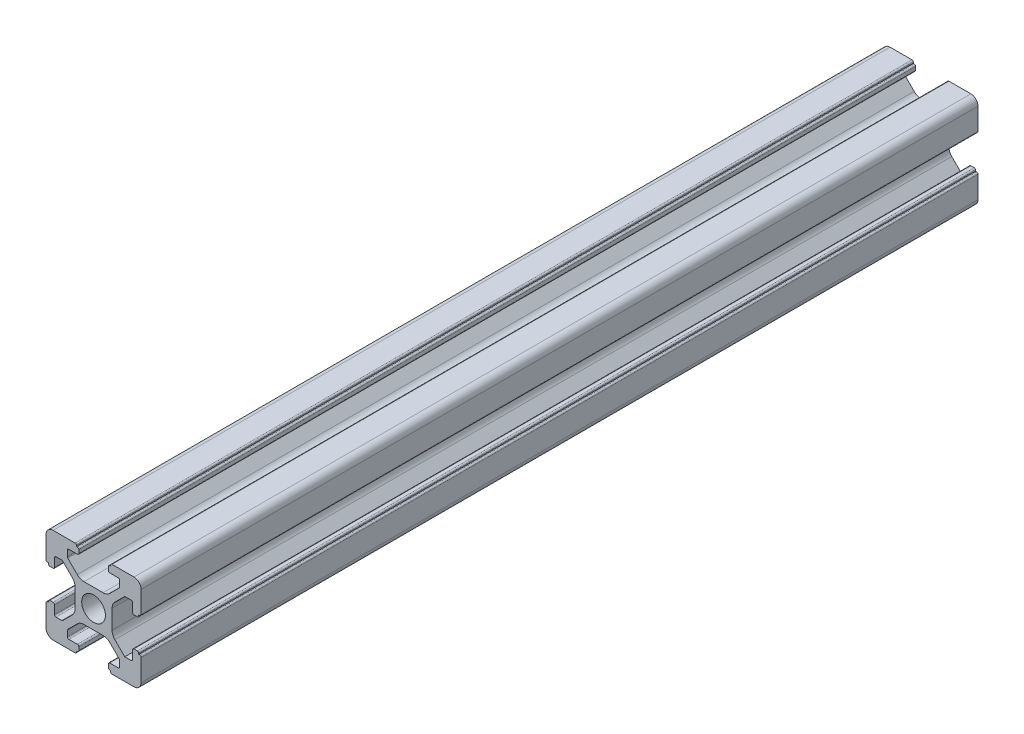
SolidWorks part; units mm, degrees
ref_plane "前视基准面" through (0, 0, 0) normal (0, 0, 1) x (1, 0, 0)
ref_plane "上视基准面" through (0, 0, 0) normal (0, 1, 0) x (1, 0, 0)
ref_plane "右视基准面" through (0, 0, 0) normal (1, 0, 0) x (0, 0, -1)
sketch "草图1" plane through (0, 0, 0) normal (0, 0, 1) x (1, 0, 0)
  line L0 (3.9, 0) -> (3.9, -2.0109)
  line L1 (4.4858, -3.4251) -> (6.5607, -5.5)
  line L2 (6.5607, -5.5) -> (7.9, -5.5)
  line L3 (8.2, -5.2) -> (8.2, -3.4)
  line L4 (8.5, -3.1) -> (9.2, -3.1)
  line L5 (9.5, -3.4) -> (9.5, -3.6)
  line L6 (9.5, -3.6) -> (9.7, -3.6)
  line L7 (10, -3.9) -> (10, -8.5)
  line L8 (8.5, -10) -> (3.9, -10)
  line L9 (3.1, -9.2) -> (3.1, -8.5)
  line L10 (3.4, -8.2) -> (5.2, -8.2)
  line L11 (5.5, -7.9) -> (5.5, -6.6849)
  line L12 (5.4121, -6.4728) -> (3.4251, -4.4858)
  line L13 (2.0109, -3.9) -> (0, -3.9)
  line L14 (0, -3.9) -> (-2.0109, -3.9)
  line L15 (-3.4251, -4.4858) -> (-5.4121, -6.4728)
  line L16 (-5.5, -6.6849) -> (-5.5, -7.9)
  line L17 (-5.2, -8.2) -> (-3.4, -8.2)
  line L18 (-3.1, -8.5) -> (-3.1, -9.2)
  line L19 (-3.9, -10) -> (-8.5, -10)
  line L20 (-10, -8.5) -> (-10, -3.9)
  line L21 (-9.7, -3.6) -> (-9.5, -3.6)
  line L22 (-9.5, -3.6) -> (-9.5, -3.4)
  line L23 (-9.2, -3.1) -> (-8.5, -3.1)
  line L24 (-8.2, -3.4) -> (-8.2, -5.2)
  line L25 (-7.9, -5.5) -> (-6.6849, -5.5)
  line L26 (-6.4728, -5.4121) -> (-4.4858, -3.4251)
  line L27 (-3.9, -2.0109) -> (-3.9, 0)
  line L28 (-3.9, 0) -> (-3.9, 2.0109)
  line L29 (-4.4858, 3.4251) -> (-6.4728, 5.4121)
  line L30 (-6.6849, 5.5) -> (-7.9, 5.5)
  line L31 (-8.2, 5.2) -> (-8.2, 3.4)
  line L32 (-8.5, 3.1) -> (-9.2, 3.1)
  line L33 (-9.5, 3.4) -> (-9.5, 3.6)
  line L34 (-9.5, 3.6) -> (-9.7, 3.6)
  line L35 (-10, 3.9) -> (-10, 8.5)
  line L36 (-8.5, 10) -> (-3.9, 10)
  line L37 (-3.6, 9.7) -> (-3.6, 9.5)
  line L38 (-3.6, 9.5) -> (-3.4, 9.5)
  line L39 (-3.1, 9.2) -> (-3.1, 8.5)
  line L40 (-3.4, 8.2) -> (-5.2, 8.2)
  line L41 (-5.5, 7.9) -> (-5.5, 6.6849)
  line L42 (-5.4121, 6.4728) -> (-3.4251, 4.4858)
  line L43 (-2.0109, 3.9) -> (0, 3.9)
  line L44 (0, 3.9) -> (2.0109, 3.9)
  line L45 (3.4251, 4.4858) -> (5.4121, 6.4728)
  line L46 (5.5, 6.6849) -> (5.5, 7.9)
  line L47 (5.2, 8.2) -> (3.4, 8.2)
  line L48 (3.1, 8.5) -> (3.1, 9.2)
  line L49 (3.4, 9.5) -> (3.6, 9.5)
  line L50 (3.6, 9.5) -> (3.6, 9.7)
  line L51 (3.9, 10) -> (8.5, 10)
  line L52 (10, 8.5) -> (10, 3.9)
  line L53 (9.7, 3.6) -> (9.5, 3.6)
  line L54 (9.5, 3.6) -> (9.5, 3.4)
  line L55 (9.2, 3.1) -> (8.5, 3.1)
  line L56 (8.2, 3.4) -> (8.2, 5.2)
  line L57 (7.9, 5.5) -> (6.6849, 5.5)
  line L58 (6.4728, 5.4121) -> (4.4858, 3.4251)
  line L59 (3.9, 2.0109) -> (3.9, 0)
  circle A0 centre (0, 0) radius 2.5
  arc A1 (3.9, -2.0109) -> (4.4858, -3.4251) centre (5.9, -2.0109) ccw
  arc A2 (7.9, -5.5) -> (8.2, -5.2) centre (7.9, -5.2) ccw
  arc A3 (8.5, -3.1) -> (8.2, -3.4) centre (8.5, -3.4) ccw
  arc A4 (9.5, -3.4) -> (9.2, -3.1) centre (9.2, -3.4) ccw
  arc A5 (10, -3.9) -> (9.7, -3.6) centre (9.7, -3.9) ccw
  arc A6 (8.5, -10) -> (10, -8.5) centre (8.5, -8.5) ccw
  arc A7 (3.6, -9.7) -> (3.9, -10) centre (3.9, -9.7) ccw
  arc A8 (3.6, -9.7) -> (3.4, -9.5) centre (3.4, -9.7) ccw
  arc A9 (3.1, -9.2) -> (3.4, -9.5) centre (3.4, -9.2) ccw
  arc A10 (3.4, -8.2) -> (3.1, -8.5) centre (3.4, -8.5) ccw
  arc A11 (5.2, -8.2) -> (5.5, -7.9) centre (5.2, -7.9) ccw
  arc A12 (5.5, -6.6849) -> (5.4121, -6.4728) centre (5.2, -6.6849) ccw
  arc A13 (3.4251, -4.4858) -> (2.0109, -3.9) centre (2.0109, -5.9) ccw
  arc A14 (-2.0109, -3.9) -> (-3.4251, -4.4858) centre (-2.0109, -5.9) ccw
  arc A15 (-5.4121, -6.4728) -> (-5.5, -6.6849) centre (-5.2, -6.6849) ccw
  arc A16 (-5.5, -7.9) -> (-5.2, -8.2) centre (-5.2, -7.9) ccw
  arc A17 (-3.1, -8.5) -> (-3.4, -8.2) centre (-3.4, -8.5) ccw
  arc A18 (-3.4, -9.5) -> (-3.1, -9.2) centre (-3.4, -9.2) ccw
  arc A19 (-3.4, -9.5) -> (-3.6, -9.7) centre (-3.4, -9.7) ccw
  arc A20 (-3.9, -10) -> (-3.6, -9.7) centre (-3.9, -9.7) ccw
  arc A21 (-10, -8.5) -> (-8.5, -10) centre (-8.5, -8.5) ccw
  arc A22 (-9.7, -3.6) -> (-10, -3.9) centre (-9.7, -3.9) ccw
  arc A23 (-9.2, -3.1) -> (-9.5, -3.4) centre (-9.2, -3.4) ccw
  arc A24 (-8.2, -3.4) -> (-8.5, -3.1) centre (-8.5, -3.4) ccw
  arc A25 (-8.2, -5.2) -> (-7.9, -5.5) centre (-7.9, -5.2) ccw
  arc A26 (-6.6849, -5.5) -> (-6.4728, -5.4121) centre (-6.6849, -5.2) ccw
  arc A27 (-4.4858, -3.4251) -> (-3.9, -2.0109) centre (-5.9, -2.0109) ccw
  arc A28 (-3.9, 2.0109) -> (-4.4858, 3.4251) centre (-5.9, 2.0109) ccw
  arc A29 (-6.4728, 5.4121) -> (-6.6849, 5.5) centre (-6.6849, 5.2) ccw
  arc A30 (-7.9, 5.5) -> (-8.2, 5.2) centre (-7.9, 5.2) ccw
  arc A31 (-8.5, 3.1) -> (-8.2, 3.4) centre (-8.5, 3.4) ccw
  arc A32 (-9.5, 3.4) -> (-9.2, 3.1) centre (-9.2, 3.4) ccw
  arc A33 (-10, 3.9) -> (-9.7, 3.6) centre (-9.7, 3.9) ccw
  arc A34 (-8.5, 10) -> (-10, 8.5) centre (-8.5, 8.5) ccw
  arc A35 (-3.6, 9.7) -> (-3.9, 10) centre (-3.9, 9.7) ccw
  arc A36 (-3.1, 9.2) -> (-3.4, 9.5) centre (-3.4, 9.2) ccw
  arc A37 (-3.4, 8.2) -> (-3.1, 8.5) centre (-3.4, 8.5) ccw
  arc A38 (-5.2, 8.2) -> (-5.5, 7.9) centre (-5.2, 7.9) ccw
  arc A39 (-5.5, 6.6849) -> (-5.4121, 6.4728) centre (-5.2, 6.6849) ccw
  arc A40 (-3.4251, 4.4858) -> (-2.0109, 3.9) centre (-2.0109, 5.9) ccw
  arc A41 (2.0109, 3.9) -> (3.4251, 4.4858) centre (2.0109, 5.9) ccw
  arc A42 (5.4121, 6.4728) -> (5.5, 6.6849) centre (5.2, 6.6849) ccw
  arc A43 (5.5, 7.9) -> (5.2, 8.2) centre (5.2, 7.9) ccw
  arc A44 (3.1, 8.5) -> (3.4, 8.2) centre (3.4, 8.5) ccw
  arc A45 (3.4, 9.5) -> (3.1, 9.2) centre (3.4, 9.2) ccw
  arc A46 (3.9, 10) -> (3.6, 9.7) centre (3.9, 9.7) ccw
  arc A47 (10, 8.5) -> (8.5, 10) centre (8.5, 8.5) ccw
  arc A48 (9.7, 3.6) -> (10, 3.9) centre (9.7, 3.9) ccw
  arc A49 (9.2, 3.1) -> (9.5, 3.4) centre (9.2, 3.4) ccw
  arc A50 (8.2, 3.4) -> (8.5, 3.1) centre (8.5, 3.4) ccw
  arc A51 (8.2, 5.2) -> (7.9, 5.5) centre (7.9, 5.2) ccw
  arc A52 (6.6849, 5.5) -> (6.4728, 5.4121) centre (6.6849, 5.2) ccw
  arc A53 (4.4858, 3.4251) -> (3.9, 2.0109) centre (5.9, 2.0109) ccw
extrude "凸台-拉伸1" add sketch "草图1" along normal blind 176 contours L42 A40 L43 L44 A41 L45 A42 L46 A43 L47 A44 L48 A45 L49 L50 A46 L51 A47 L52 A48 L53 L54 A49 L55 A50 L56 A51 L57 A52 L58 A53 L59 L0 A1 L1 L2 A2 L3 A3 L4 A4 L5 L6 A5 L7 A6 L8 A7 A8 A9 L9 A10 L10 A11 L11 A12 L12 A13 L13 L14 A14 L15 A15 L16 A16 L17 A17 L18 A18 A19 A20 L19 A21 L20 A22 L21 L22 A23 L23 A24 L24 A25 L25 A26 L26 A27 L27 L28 A28 L29 A29 L30 A30 L31 A31 L32 A32 L33 L34 A33 L35 A34 L36 A35 L37 L38 A36 L39 A37 L40 A38 L41 A39 | A0
